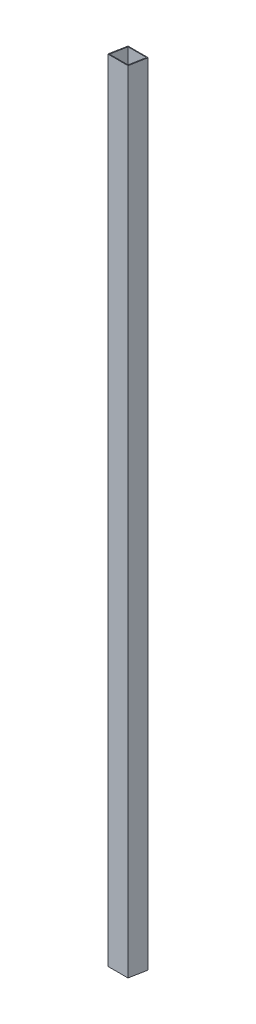
SolidWorks part; units mm, degrees
ref_plane "Front Plane" through (0, 0, 0) normal (0, 0, 1) x (1, 0, 0)
ref_plane "Top Plane" through (0, 0, 0) normal (0, 1, 0) x (1, 0, 0)
ref_plane "Right Plane" through (0, 0, 0) normal (1, 0, 0) x (0, 0, -1)
sketch "Sketch1" plane through (0, 0, 0) normal (0, 1, 0) x (1, 0, 0)
  line L0 (-11.5, 11.5) -> (11.5, 11.5)
  line L1 (-12.5, -12.5) -> (12.5, -12.5)
  line L2 (-12.5, -12.5) -> (-12.5, 12.5)
  line L3 (-12.5, 12.5) -> (12.5, 12.5)
  line L4 (12.5, -12.5) -> (12.5, 12.5)
  line L5 (-12.5, -12.5) -> (12.5, 12.5) construction
  line L6 (-12.5, 12.5) -> (12.5, -12.5) construction
  line L7 (11.5, -11.5) -> (11.5, 11.5)
  line L8 (-11.5, -11.5) -> (11.5, -11.5)
  line L9 (-11.5, -11.5) -> (-11.5, 11.5)
  point P0 (0, 0)
  dimension "D2" = 25
  dimension "D3" = 25
  dimension "D1" = 1
extrude "Boss-Extrude1" add sketch "Sketch1" along normal blind 1200
sketch "Sketch2" plane through (12.5, 0, 0) normal (1, 0, 0) x (0, 0, -1)
  line L0 (12.5, 0) -> (-12.5, 3.9596)
  line L1 (-12.5, 1200) -> (-12.5, 0) construction
  line L2 (-12.5, 3.9596) -> (-12.5, 0)
  line L3 (-12.5, 0) -> (12.5, 0)
  line L4 (12.5, 1200) -> (-12.5, 1200)
  line L5 (-12.5, 1200) -> (-12.5, 980.9885)
  line L6 (-12.5, 980.9885) -> (12.5, 977.0288)
  line L7 (12.5, 1200) -> (12.5, 0) construction
  line L8 (12.5, 977.0288) -> (12.5, 1200)
  dimension "D1" = 9
  dimension "D2" = 965
extrude "Cut-Extrude1" cut sketch "Sketch2" against normal through all
